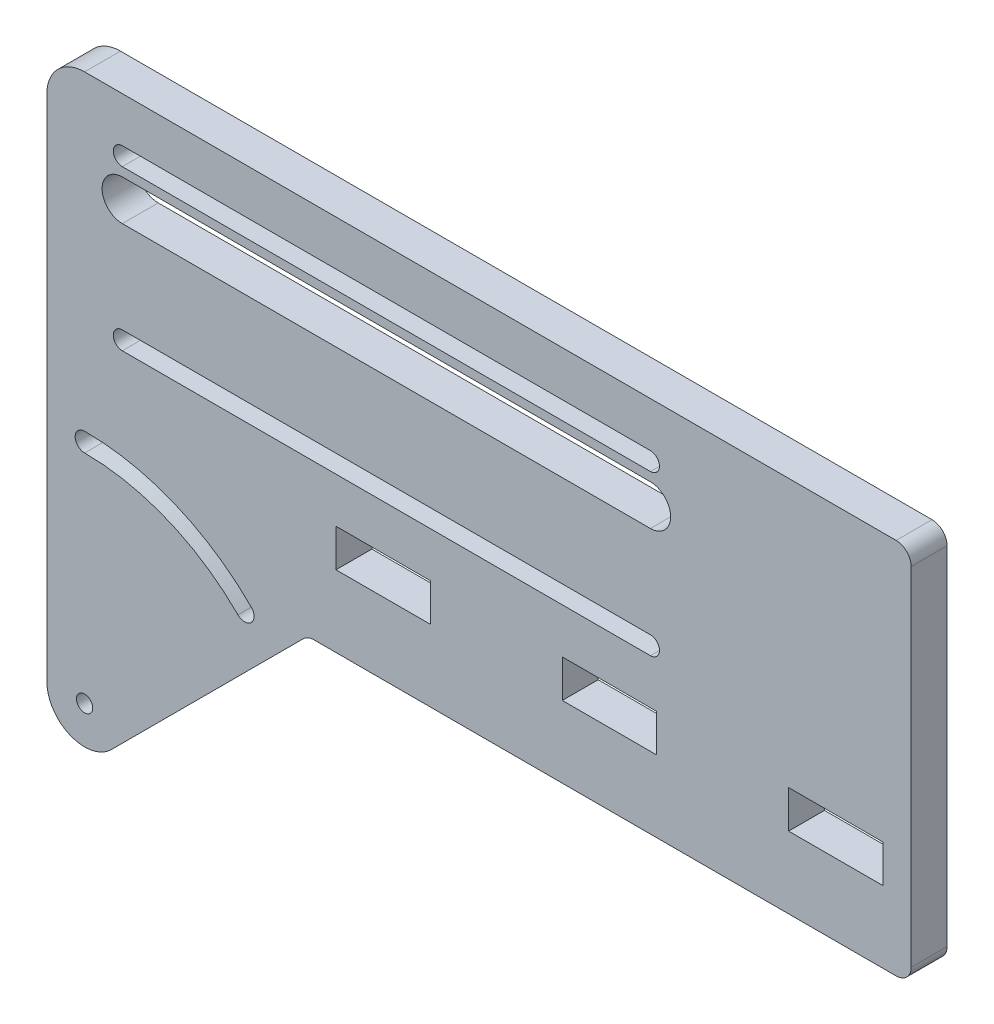
SolidWorks part; units mm, degrees
ref_plane "Front Plane" through (0, 0, 0) normal (0, 0, 1) x (1, 0, 0)
ref_plane "Top Plane" through (0, 0, 0) normal (0, 1, 0) x (1, 0, 0)
ref_plane "Right Plane" through (0, 0, 0) normal (1, 0, 0) x (0, 0, -1)
sketch "Sketch1" plane through (0, 0, 0) normal (0, 0, 1) x (1, 0, 0)
  line L0 (0, 0) -> (26.9408, 26.9408) construction
  line L1 (0, 0) -> (0, 38.1) construction
  line L2 (-6.35, 85.725) -> (-6.35, 0)
  line L3 (4.4901, -4.4901) -> (31.4309, 22.4506)
  line L4 (0, 0) -> (37.5553, 0) construction
  line L5 (37.5553, 0) -> (37.5553, 28.575) construction
  line L6 (36.8113, 27.8311) -> (31.4309, 22.4506)
  line L7 (38.6074, 28.575) -> (136.6153, 28.575)
  line L10 (139.1553, 31.115) -> (139.1553, 89.535)
  line L12 (136.6153, 92.075) -> (0, 92.075)
  circle A0 centre (0, 0) radius 1.3716
  arc A1 (-6.35, 0) -> (4.4901, -4.4901) centre (0, 0) ccw
  circle A2 centre (0, 0) radius 38.1 construction
  arc A3 (25.8182, 25.8182) -> (0, 36.5125) centre (0, 0) ccw
  arc A4 (28.0633, 28.0633) -> (0, 39.6875) centre (0, 0) ccw
  arc A5 (25.8182, 25.8182) -> (28.0633, 28.0633) centre (26.9408, 26.9408) ccw
  arc A6 (0, 39.6875) -> (0, 36.5125) centre (0, 38.1) ccw
  circle A9 centre (0, 0) radius 31.75 construction
  arc A10 (31.4309, 31.4309) -> (0, 44.45) centre (0, 0) ccw construction
  arc A12 (31.0411, 22.0921) -> (31.4309, 31.4309) centre (26.9408, 26.9408) ccw construction
  circle A13 centre (0, 38.1) radius 6.35 construction
  arc A14 (0, 44.45) -> (31.4309, 31.4309) centre (0, 0) ccw construction
  arc A15 (38.6074, 28.575) -> (36.8113, 27.8311) centre (38.6074, 26.035) ccw
  arc A16 (136.6153, 28.575) -> (139.1553, 31.115) centre (136.6153, 31.115) ccw
  arc A19 (139.1553, 89.535) -> (136.6153, 92.075) centre (136.6153, 89.535) ccw
  arc A20 (-6.35, 85.725) -> (0, 92.075) centre (0, 85.725) cw
  point P3 (8.9803, 0)
  point P5 (0, 0)
  point P12 (26.4872, 17.5069)
  point P29 (-6.35, 31.1085)
  dimension "D1" = 2.7432
  dimension "D2" = 12.7
  dimension "D3" = 76.2
  dimension "D4" = 79.375
  dimension "D5" = 73.025
  dimension "D6" = 45
  dimension "D7" = 63.5
  dimension "D8" = 88.9
  dimension "D9" = 6.35
  dimension "D13" = 2.54
  dimension "D12" = 12.7
  dimension "D17" = 2.54
  dimension "D10" = 28.575
  dimension "D11" = 28.575
  dimension "D14" = 63.5
  dimension "D16" = 101.6
extrude "Boss-Extrude1" add sketch "Sketch1" along normal blind 6.0452
sketch "Sketch2" plane through (0, 0, 6.0452) normal (0, 0, 1) x (1, 0, 0)
  line L0 (38.6074, 28.575) -> (136.6153, 28.575) construction
  line L1 (118.5178, 46.99) -> (134.3928, 46.99)
  line L2 (118.5178, 46.99) -> (118.5178, 40.64)
  line L3 (118.5178, 40.64) -> (134.3928, 40.64)
  line L4 (134.3928, 46.99) -> (134.3928, 40.64)
  line L5 (139.1553, 31.115) -> (139.1553, 89.535) construction
  line L6 (80.4178, 46.99) -> (80.4178, 40.64)
  line L7 (80.4178, 46.99) -> (96.2928, 46.99)
  line L8 (96.2928, 46.99) -> (96.2928, 40.64)
  line L9 (80.4178, 40.64) -> (96.2928, 40.64)
  line L10 (42.3178, 46.99) -> (42.3178, 40.64)
  line L11 (42.3178, 46.99) -> (58.1928, 46.99)
  line L12 (58.1928, 46.99) -> (58.1928, 40.64)
  line L13 (42.3178, 40.64) -> (58.1928, 40.64)
  line L14 (118.5178, 46.99) -> (80.4178, 46.99) construction
  dimension "D1" = 15.875
  dimension "D2" = 6.35
  dimension "D3" = 12.065
  dimension "D4" = 4.7625
  dimension "D5" = 38.1
  dimension "D6" = 3
extrude "Cut-Extrude1" cut sketch "Sketch2" against normal blind 6.0452
sketch "Sketch3" plane through (0, 0, 0) normal (0, 0, -1) x (-1, 0, 0)
  line L0 (6.35, 85.725) -> (6.35, 0) construction
  line L1 (-95.25, 82.9564) -> (-95.25, 56.1086) construction
  line L2 (-42.3178, 46.99) -> (-42.3178, 92.075) construction
  line L3 (-136.6153, 92.075) -> (0, 92.075) construction
  line L4 (-95.25, 84.4804) -> (-6.35, 84.4804)
  line L5 (-6.35, 81.4324) -> (-95.25, 81.4324)
  line L6 (-95.25, 57.6326) -> (-6.35, 57.6326)
  line L7 (-6.35, 54.5846) -> (-95.25, 54.5846)
  line L8 (-95.25, 73.1266) -> (-6.35, 73.1266)
  line L9 (-95.25, 79.9338) -> (-6.35, 79.9338)
  arc A0 (-6.35, 81.4324) -> (-6.35, 84.4804) centre (-6.35, 82.9564) ccw
  arc A1 (-6.35, 54.5846) -> (-6.35, 57.6326) centre (-6.35, 56.1086) ccw
  arc A2 (-95.25, 84.4804) -> (-95.25, 81.4324) centre (-95.25, 82.9564) ccw
  arc A3 (-95.25, 57.6326) -> (-95.25, 54.5846) centre (-95.25, 56.1086) ccw
  arc A4 (-6.35, 73.1266) -> (-6.35, 79.9338) centre (-6.35, 76.5302) ccw
  arc A5 (-95.25, 79.9338) -> (-95.25, 73.1266) centre (-95.25, 76.5302) ccw
  point P15 (-95.25, 69.5325)
  point P16 (-42.3178, 69.5325)
  point P29 (-11.1017, 79.9338)
  dimension "D1" = 3.048
  dimension "D2" = 3.048
  dimension "D4" = 3.048
  dimension "D5" = 3.048
  dimension "D9" = 6.8072
  dimension "D10" = 6.8072
  dimension "D3" = 26.8478
  dimension "D6" = 88.9
  dimension "D7" = 12.7
  dimension "D8" = 6.4262
extrude "Cut-Extrude2" cut sketch "Sketch3" against normal blind 7.62
